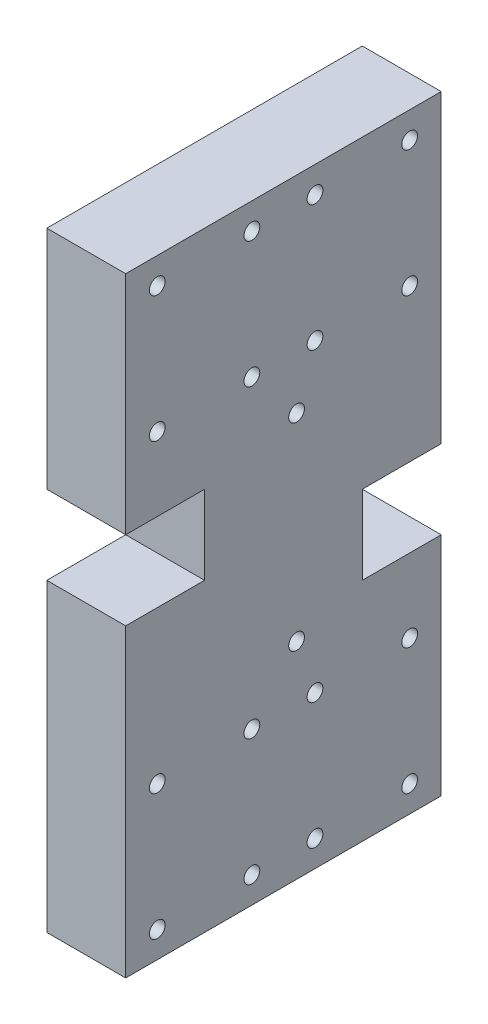
SolidWorks part; units mm, degrees
ref_plane "Alzado" through (0, 0, 0) normal (0, 0, 1) x (1, 0, 0)
ref_plane "Planta" through (0, 0, 0) normal (0, 1, 0) x (1, 0, 0)
ref_plane "Vista lateral" through (0, 0, 0) normal (1, 0, 0) x (0, 0, -1)
sketch "Croquis1" plane through (0, 0, 0) normal (1, 0, 0) x (0, 0, -1)
  line L0 (30, 116) -> (30, 0) construction
  line L1 (0, 0) -> (60, 0)
  line L2 (0, 0) -> (0, 116)
  line L3 (0, 116) -> (60, 116)
  line L4 (60, 0) -> (60, 116)
  line L5 (0, 58) -> (60, 58) construction
  line L6 (32.5, 39.2) -> (32.5, 58) construction
  line L7 (32.5, 58) -> (32.5, 76.8) construction
  circle A0 centre (54, 5) radius 1.5
  circle A1 centre (36, 5) radius 1.5
  circle A2 centre (36, 29) radius 1.5
  circle A3 centre (54, 29) radius 1.5
  circle A4 centre (24, 29) radius 1.5
  circle A5 centre (24, 5) radius 1.5
  circle A6 centre (6, 5) radius 1.5
  circle A7 centre (6, 29) radius 1.5
  circle A8 centre (6, 87) radius 1.5
  circle A9 centre (6, 111) radius 1.5
  circle A10 centre (24, 111) radius 1.5
  circle A11 centre (24, 87) radius 1.5
  circle A12 centre (36, 87) radius 1.5
  circle A13 centre (36, 111) radius 1.5
  circle A14 centre (54, 111) radius 1.5
  circle A15 centre (54, 87) radius 1.5
  circle A16 centre (32.5, 76.8) radius 1.5
  circle A17 centre (32.5, 39.2) radius 1.5
  dimension "D3" = 3
  dimension "D8" = 3
  dimension "D1" = 116
  dimension "D2" = 60
  dimension "D4" = 5
  dimension "D5" = 6
  dimension "D6" = 24
  dimension "D7" = 18
  dimension "D9" = 2.5
  dimension "D10" = 37.6
extrude "Saliente-Extruir1" add sketch "Croquis1" along normal blind 15
sketch "Croquis2" plane through (15, 0, 0) normal (1, 0, 0) x (0, 0, -1)
  line L0 (0, 58) -> (60, 58) construction
  line L1 (0, 116) -> (0, 0) construction
  line L2 (60, 0) -> (60, 116) construction
  line L4 (0, 58) -> (15, 58)
  line L5 (0, 58) -> (0, 73)
  line L6 (0, 73) -> (15, 73)
  line L7 (15, 58) -> (15, 73)
  line L8 (60, 58) -> (45, 58)
  line L9 (60, 58) -> (60, 43)
  line L10 (60, 43) -> (45, 43)
  line L11 (45, 58) -> (45, 43)
  dimension "D1" = 15
  dimension "D2" = 15
extrude "Cortar-Extruir1" cut sketch "Croquis2" against normal through all
